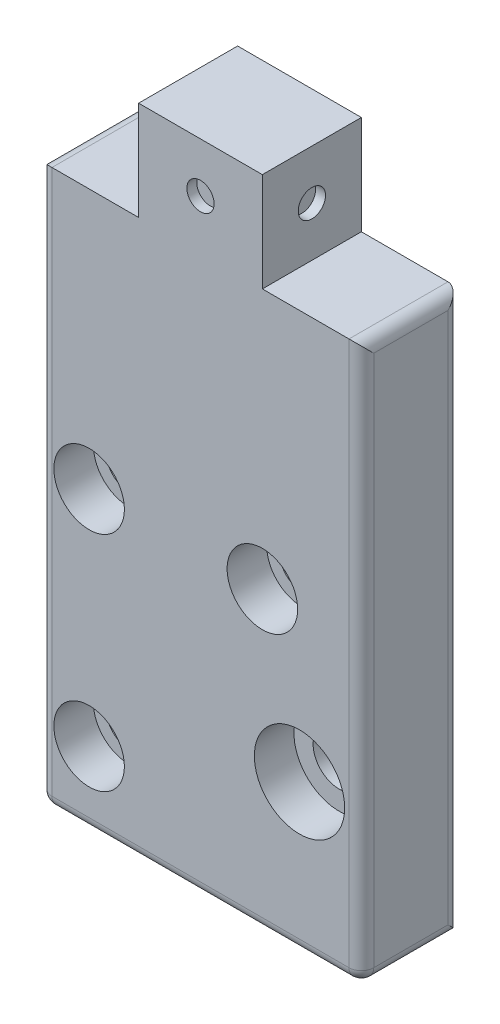
SolidWorks part; units mm, degrees
ref_plane "Front Plane" through (0, 0, 0) normal (0, 0, 1) x (1, 0, 0)
ref_plane "Top Plane" through (0, 0, 0) normal (0, 1, 0) x (1, 0, 0)
ref_plane "Right Plane" through (0, 0, 0) normal (1, 0, 0) x (0, 0, -1)
sketch "Sketch1" plane through (0, 0, 0) normal (0, 0, 1) x (1, 0, 0)
  line L0 (0, 57.15) -> (10.16, 57.15)
  line L1 (0, 0) -> (33.02, 0)
  line L5 (10.16, 57.15) -> (10.16, 67.31)
  line L6 (10.16, 67.31) -> (22.86, 67.31)
  line L7 (22.86, 67.31) -> (22.86, 57.15)
  line L8 (22.86, 57.15) -> (33.02, 57.15)
  line L9 (0, 57.15) -> (0, 0)
  line L10 (33.02, 57.15) -> (33.02, 0)
  line L11 (0, 45.5713) -> (10.16, 45.5713) construction
  line L12 (10.16, 45.5713) -> (10.16, 25.4) construction
  circle A0 centre (5.08, 7.62) radius 2.286
  circle A1 centre (5.08, 30.48) radius 2.286
  circle A2 centre (26.67, 15.24) radius 2.667
  circle A3 centre (22.86, 30.48) radius 2.286
  point P11 (29.337, 15.24)
  point P12 (24.003, 15.24)
  dimension "D3" = 7.62
  dimension "D5" = 4.572
  dimension "D6" = 4.572
  dimension "D8" = 29.337
  dimension "D9" = 10.16
  dimension "D10" = 10.16
  dimension "D13" = 17.78
  dimension "D14" = 4.572
  dimension "D16" = 15.24
  dimension "D1" = 33.02
  dimension "D2" = 5.08
  dimension "D4" = 24.003
  dimension "D7" = 22.86
  dimension "D11" = 10.16
  dimension "D12" = 25.4
  dimension "D15" = 5.08
  dimension "D17" = 57.15
  dimension "D18" = 12.7
extrude "Boss-Extrude1" add sketch "Sketch1" along normal blind 10.16
sketch "Sketch3" plane through (0, 0, 10.16) normal (0, 0, -1) x (-1, 0, 0)
  line L0 (-16.51, 67.31) -> (-16.51, 62.23) construction
  line L1 (-22.86, 67.31) -> (-10.16, 67.31) construction
  line L2 (-16.51, 62.23) -> (-10.16, 62.23) construction
  line L3 (-10.16, 67.31) -> (-10.16, 57.15) construction
  circle A0 centre (-16.51, 62.23) radius 1.397
  dimension "D1" = 2.794
sketch "Sketch7" plane through (0, 0, 10.16) normal (0, 0, 1) x (1, 0, 0)
  circle A0 centre (5.08, 30.48) radius 3.6195
  circle A1 centre (22.86, 30.48) radius 3.6195
  circle A2 centre (5.08, 7.62) radius 3.6195
  circle A3 centre (26.67, 15.24) radius 4.6355
  point P0 (5.08, 30.48)
  point P1 (5.08, 7.62)
  point P3 (22.86, 30.48)
  point P12 (26.67, 15.24)
  dimension "D1" = 7.239
  dimension "D2" = 7.239
  dimension "D3" = 7.239
  dimension "D4" = 9.271
extrude "Cut-Extrude1" cut sketch "Sketch7" against normal blind 4.064
extrude "Cut-Extrude2" cut sketch "Sketch3" along normal blind 1.016
sketch "Sketch8" plane through (22.86, 0, 0) normal (1, 0, 0) x (0, 0, -1)
  line L0 (-5.08, 62.23) -> (0, 62.23) construction
  line L1 (0, 57.15) -> (0, 67.31) construction
  line L2 (-5.08, 67.31) -> (-5.08, 62.23) construction
  line L3 (-10.16, 67.31) -> (0, 67.31) construction
  circle A0 centre (-5.08, 62.23) radius 1.397
  dimension "D1" = 2.794
extrude "Cut-Extrude3" cut sketch "Sketch8" against normal blind 1.016
sketch "Sketch9" plane through (10.16, 0, 0) normal (-1, 0, 0) x (0, 0, 1)
  line L0 (5.08, 62.23) -> (5.08, 67.31) construction
  line L1 (10.16, 67.31) -> (0, 67.31) construction
  line L2 (5.08, 62.23) -> (10.16, 62.23) construction
  line L3 (10.16, 67.31) -> (10.16, 57.15) construction
  circle A0 centre (5.08, 62.23) radius 1.397
  dimension "D1" = 2.794
extrude "Cut-Extrude4" cut sketch "Sketch9" against normal blind 1.016
fillet "Fillet1" radius 1.27 8 edges at (0, 0, 5.08) (33.02, 28.575, 0) (33.02, 0, 5.08) (0, 57.15, 5.08) (33.02, 57.15, 5.08) (0, 28.575, 10.16) (33.02, 28.575, 10.16) (16.51, 0, 10.16)
